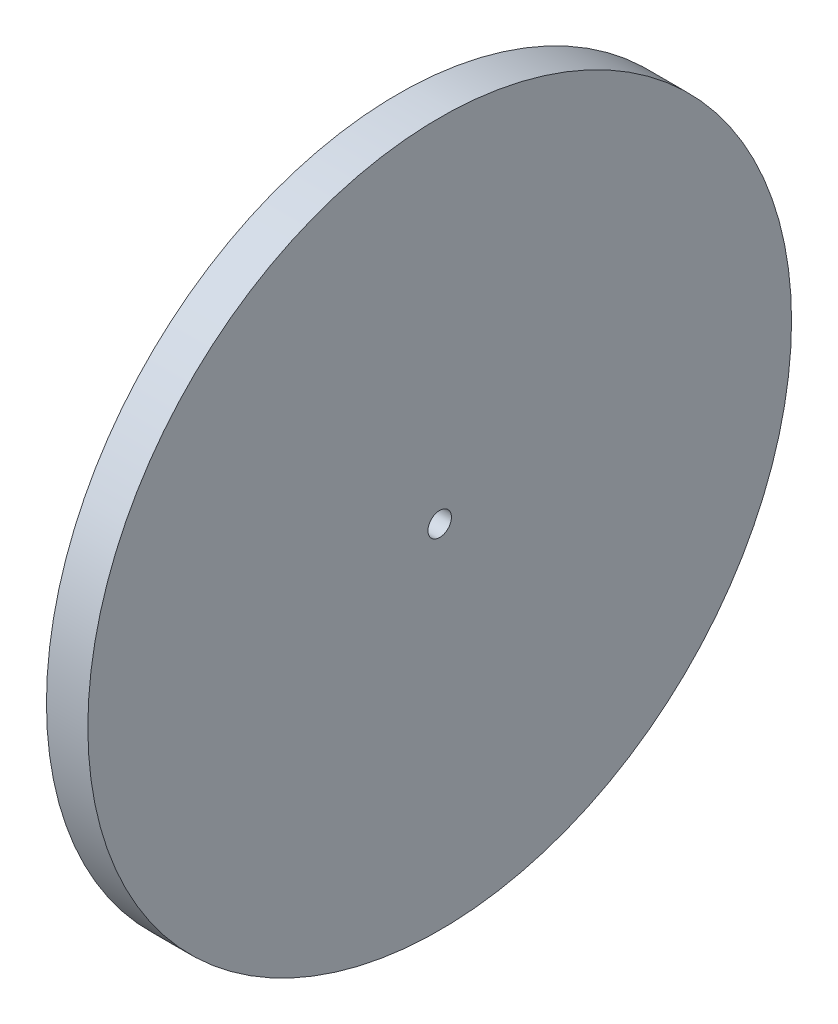
SolidWorks part; units mm, degrees
ref_plane "Front Plane" through (0, 0, 0) normal (0, 0, 1) x (1, 0, 0)
ref_plane "Top Plane" through (0, 0, 0) normal (0, 1, 0) x (1, 0, 0)
ref_plane "Right Plane" through (0, 0, 0) normal (1, 0, 0) x (0, 0, -1)
sketch "Sketch1" plane through (0, 0, 0) normal (1, 0, 0) x (0, 0, -1)
  circle A0 centre (-1.7759, 2.6639) radius 27
  circle A1 centre (-1.7759, 2.6639) radius 0.9
extrude "Extrude1" add sketch "Sketch1" along normal blind 3.175
